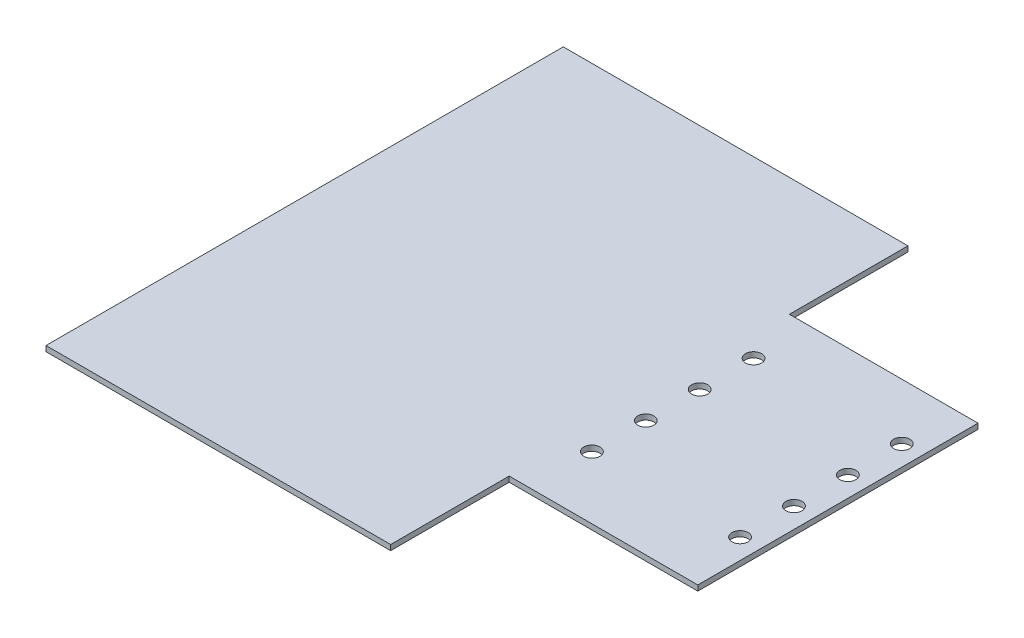
SolidWorks part; units mm, degrees
ref_plane "Спереди" through (0, 0, 0) normal (0, 0, 1) x (1, 0, 0)
ref_plane "Сверху" through (0, 0, 0) normal (0, 1, 0) x (1, 0, 0)
ref_plane "Справа" through (0, 0, 0) normal (1, 0, 0) x (0, 0, -1)
sketch "Эскиз1" plane through (0, 0, 0) normal (0, 1, 0) x (1, 0, 0)
  line L0 (15, -26) -> (15, -48)
  line L4 (15, 48) -> (15, 26)
  line L5 (50, 26) -> (15, 26)
  line L6 (50, 26) -> (50, -26)
  line L7 (50, -26) -> (15, -26)
  line L8 (-48.9591, 48) -> (15, 48)
  line L9 (-48.9591, 48) -> (-48.9591, -48)
  line L10 (-50, 0) -> (50, 0) construction
  line L11 (-48.9591, -48) -> (15, -48)
extrude "Бобышка-Вытянуть1" add sketch "Эскиз1" along normal blind 1
sketch "Эскиз2" plane through (0, 1, 0) normal (0, 1, 0) x (1, 0, 0)
  circle A0 centre (46.25, -14.4) radius 1.5
  circle A1 centre (18.75, -14.4) radius 1.5
  circle A2 centre (18.75, -4.4) radius 1.5
  circle A3 centre (46.25, -4.4) radius 1.5
  circle A4 centre (18.75, 5.6) radius 1.5
  circle A5 centre (46.25, 5.6) radius 1.5
  circle A6 centre (18.75, 15.6) radius 1.5
  circle A7 centre (46.25, 15.6) radius 1.5
  dimension "D1" = 4
extrude "Вырез-Вытянуть1" cut sketch "Эскиз2" against normal blind 10
